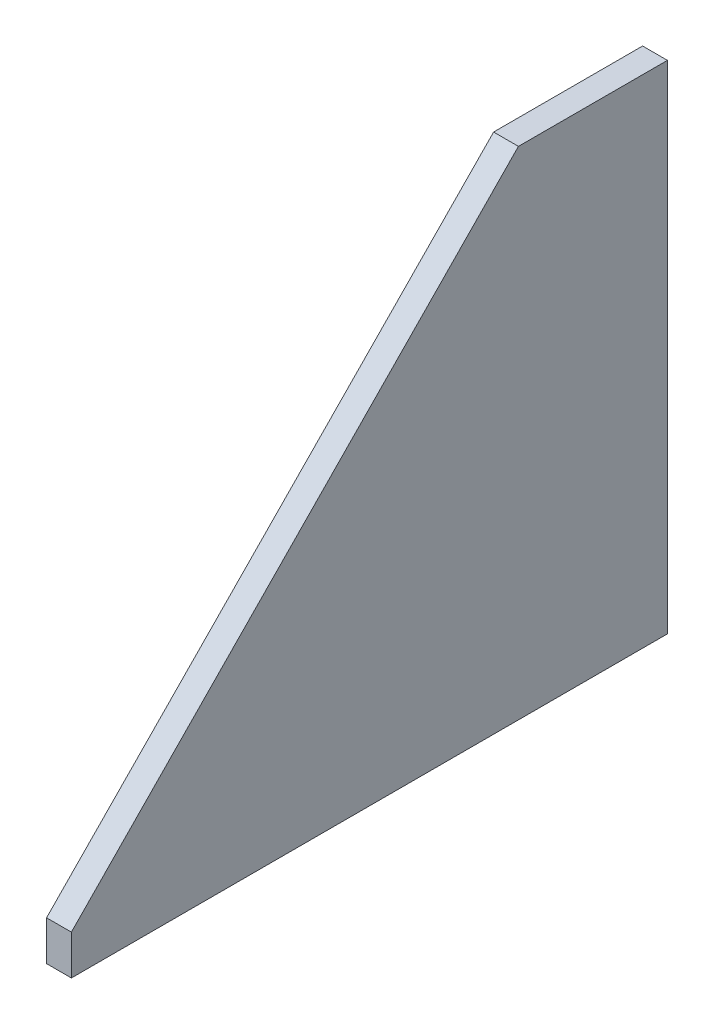
SolidWorks part; units mm, degrees
material "Very Low Density PE (SS)"
ref_plane "Front Plane" through (0, 0, 0) normal (0, 0, 1) x (1, 0, 0)
ref_plane "Top Plane" through (0, 0, 0) normal (0, 1, 0) x (1, 0, 0)
ref_plane "Right Plane" through (0, 0, 0) normal (1, 0, 0) x (0, 0, -1)
sketch "Sketch1" plane through (0, 0, 0) normal (1, 0, 0) x (0, 0, -1)
  line L0 (0, 0) -> (120, 0)
  line L1 (120, 0) -> (120, 100)
  line L2 (120, 100) -> (90, 100)
  line L3 (90, 100) -> (0, 8)
  line L4 (0, 8) -> (0, 0)
  dimension "D1" = 8
  dimension "D2" = 120
  dimension "D3" = 100
  dimension "D4" = 30
extrude "Boss-Extrude1" add sketch "Sketch1" along normal mid plane 5
